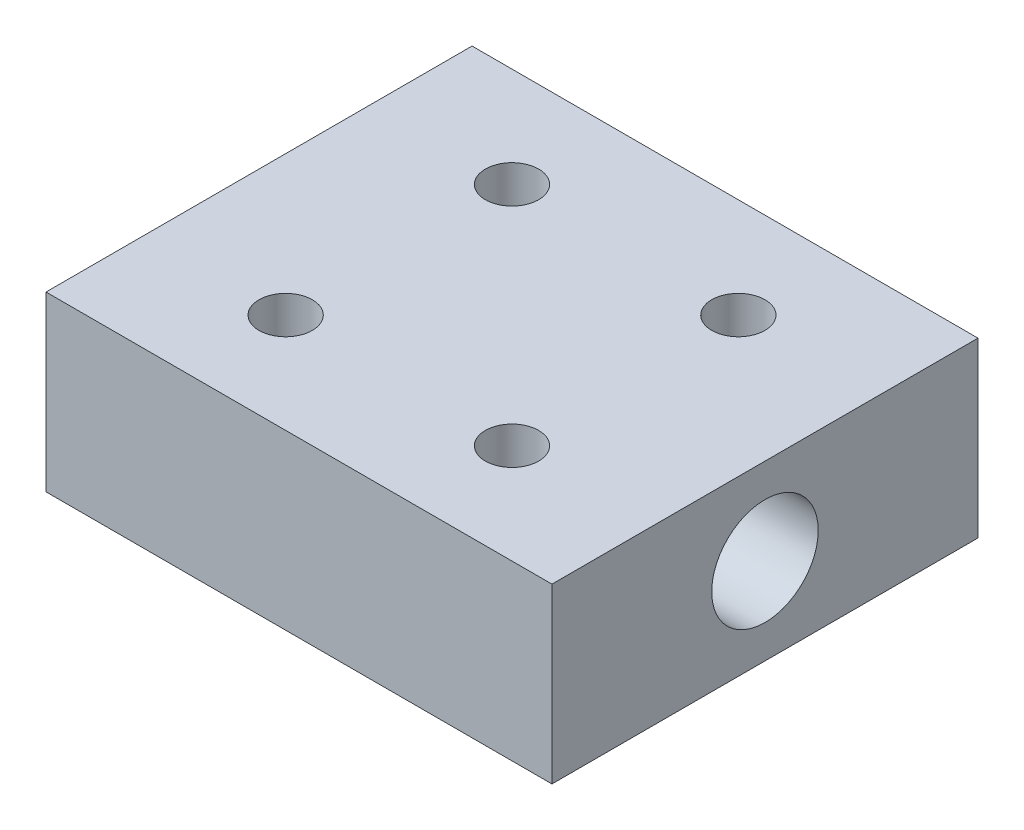
SolidWorks part; units mm, degrees
ref_plane "Front Plane" through (0, 0, 0) normal (0, 0, 1) x (1, 0, 0)
ref_plane "Top Plane" through (0, 0, 0) normal (0, 1, 0) x (1, 0, 0)
ref_plane "Right Plane" through (0, 0, 0) normal (1, 0, 0) x (0, 0, -1)
sketch "Sketch1" plane through (0, 0, 0) normal (0, 1, 0) x (1, 0, 0)
  line L1 (-19, -16) -> (19, -16)
  line L2 (-19, -16) -> (-19, 16)
  line L3 (-19, 16) -> (19, 16)
  line L4 (19, -16) -> (19, 16)
  line L5 (-19, -16) -> (19, 16) construction
  line L6 (-19, 16) -> (19, -16) construction
  point P0 (0, 0)
  dimension "D1" = 32
  dimension "D2" = 38
extrude "Boss-Extrude1" add sketch "Sketch1" along normal blind 13
sketch "Sketch2" plane through (0, 13, 0) normal (0, 1, 0) x (1, 0, 0)
  line L0 (0, 0) -> (22.2679, 0) construction
  line L1 (0, 0) -> (0, 13.5727) construction
  circle A0 centre (8.5, 8.5) radius 2
  circle A1 centre (-8.5, 8.5) radius 2
  circle A2 centre (-8.5, -8.5) radius 2
  circle A3 centre (8.5, -8.5) radius 2
  dimension "D1" = 4
  dimension "D2" = 17
  dimension "D3" = 17
extrude "Cut-Extrude1" cut sketch "Sketch2" against normal blind 8
sketch "Sketch3" plane through (19, 0, 0) normal (1, 0, 0) x (0, 0, -1)
  line L0 (16, 13) -> (16, 0) construction
  circle A0 centre (0, 6.5) radius 4
  point P8 (16, 6.5)
  dimension "D1" = 8
extrude "Cut-Extrude2" cut sketch "Sketch3" against normal through all
